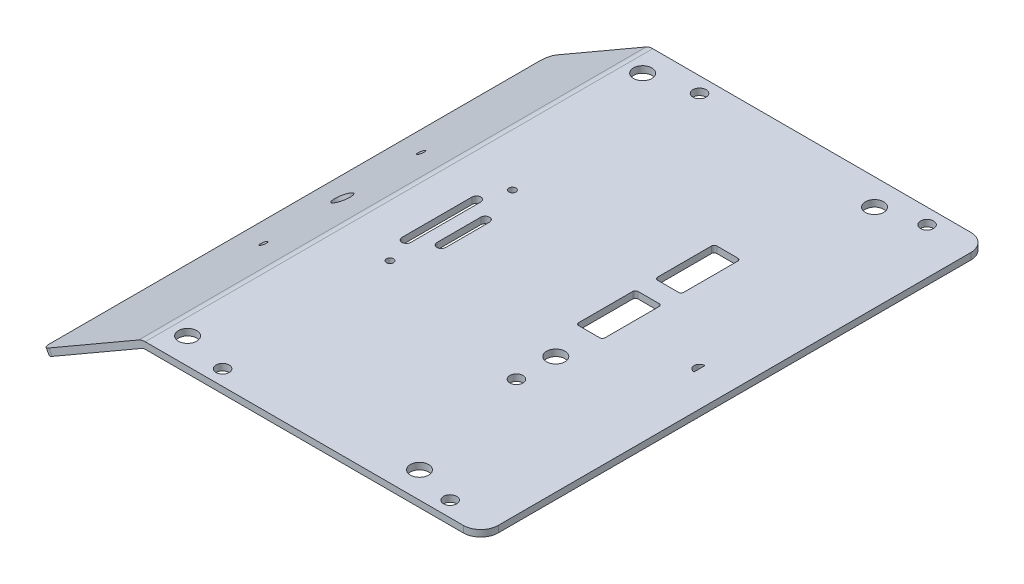
SolidWorks part; units mm, degrees
ref_plane "Alzado" through (0, 0, 0) normal (0, 0, 1) x (1, 0, 0)
ref_plane "Planta" through (0, 0, 0) normal (0, 1, 0) x (1, 0, 0)
ref_plane "Vista lateral" through (0, 0, 0) normal (1, 0, 0) x (0, 0, -1)
ref_plane "Plano1" through (0, 0, -57) normal (0, 0, -1) x (-1, 0, 0)
sketch "Croquis1" plane through (0, 0, -57) normal (0, 0, -1) x (-1, 0, 0)
  line L0 (58.4497, -13.25) -> (35.5, 0)
  line L1 (35.5, 0) -> (-38, 0)
  line L2 (-38, 0) -> (-38, -1.5)
  line L3 (-38, -1.5) -> (35.0981, -1.5)
  line L4 (35.0981, -1.5) -> (57.6997, -14.549)
  line L5 (57.6997, -14.549) -> (58.4497, -13.25)
extrude "Saliente-Extruir1" add sketch "Croquis1" against normal blind 116
sketch "Croquis2" plane through (0, 0, 0) normal (0, 1, 0) x (-1, 0, 0)
  line L0 (-17.07, -25.275) -> (-11.07, -25.275)
  line L1 (-11.07, -25.275) -> (-11.07, -11.725)
  line L2 (-11.07, -11.725) -> (-17.07, -11.725)
  line L3 (-17.07, -11.725) -> (-17.07, -25.275)
extrude "Cortar-Extruir1" cut sketch "Croquis2" against normal through all
sketch "Croquis3" plane through (0, 0, 0) normal (0, 1, 0) x (-1, 0, 0)
  line L0 (-11.07, -7.275) -> (-11.07, 6.275)
  line L1 (-11.07, 6.275) -> (-17.07, 6.275)
  line L2 (-17.07, 6.275) -> (-17.07, -7.275)
  line L3 (-17.07, -7.275) -> (-11.07, -7.275)
extrude "Cortar-Extruir2" cut sketch "Croquis3" against normal through all
sketch "Croquis4" plane through (0, 0, 0) normal (0, 1, 0) x (-1, 0, 0)
  line L0 (21, -4) -> (21, 6)
  line L1 (19, 6) -> (19, -4)
  arc A0 (19, -4) -> (21, -4) centre (20, -4) ccw
  arc A1 (21, 6) -> (19, 6) centre (20, 6) ccw
extrude "Cortar-Extruir3" cut sketch "Croquis4" against normal through all
sketch "Croquis5" plane through (0, -1.5, 0) normal (0, -1, 0) x (1, 0, 0)
  line L0 (-24, -7) -> (-24, 9)
  line L1 (-26, 9) -> (-26, -7)
  arc A0 (-26, -7) -> (-24, -7) centre (-25, -7) ccw
  arc A1 (-24, 9) -> (-26, 9) centre (-25, 9) ccw
extrude "Cortar-Extruir4" cut sketch "Croquis5" against normal through all
hole_wizard "Diámetro de taladro Ø2.5 (2.5)1" positions "Croquis7" profile "Croquis6" hole size "Ø2.5" standard "Ansi Metric"
sketch "Croquis7" plane through (0, -1.5, 0) normal (0, -1, 0) x (-1, 0, 0)
  point P0 (-34, -1)
sketch "Croquis6" plane through (34, -1.5, 1) normal (1, 0, 0) x (0, 0, -1)
  line L0 (0, 0) -> (0, 1.5)
  line L1 (0, 1.5) -> (1.25, 1.5)
  line L2 (1.25, 1.5) -> (1.25, 0)
  line L5 (1.25, 0) -> (0, 0)
  line L11 (0, -6.35) -> (0, 107.95) construction
  dimension "Diámetro de taladro hasta el siguiente" = 2.5
  dimension "Profundidad de taladro hasta el siguiente" = 1.5
hole_wizard "Diámetro de taladro Ø3.0 (3)1" positions "Croquis9" profile "Croquis8" hole size "Ø3.0" standard "Ansi Metric"
sketch "Croquis9" plane through (0, -1.5, 0) normal (0, -1, 0) x (-1, 0, 0)
  point P0 (-15.15, -24)
  point P1 (-31.5, 53.5)
  point P2 (20.5, -55.5)
  point P3 (-31.5, -55.5)
  point P4 (20.5, 53.5)
sketch "Croquis8" plane through (15.15, -1.5, 24) normal (1, 0, 0) x (0, 0, -1)
  line L0 (0, 0) -> (0, 1.5)
  line L1 (0, 1.5) -> (1.5, 1.5)
  line L2 (1.5, 1.5) -> (1.5, 0)
  line L5 (1.5, 0) -> (0, 0)
  line L11 (0, -6.35) -> (0, 107.95) construction
  dimension "Diámetro de taladro hasta el siguiente" = 3
  dimension "Profundidad de taladro hasta el siguiente" = 1.5
hole_wizard "Diámetro de taladro Ø1.6 (1.6)1" positions "Croquis11" profile "Croquis10" hole size "Ø1.6" standard "Ansi Metric"
sketch "Croquis11" plane through (0, -1.5, 0) normal (0, -1, 0) x (-1, 0, 0)
  point P0 (22.75, -15)
  point P1 (22.75, 13)
sketch "Croquis10" plane through (-22.75, -1.5, 15) normal (1, 0, 0) x (0, 0, -1)
  line L0 (0, 0) -> (0, 1.5)
  line L1 (0, 1.5) -> (0.8, 1.5)
  line L2 (0.8, 1.5) -> (0.8, 0)
  line L5 (0.8, 0) -> (0, 0)
  line L11 (0, -6.35) -> (0, 107.95) construction
  dimension "Diámetro de taladro hasta el siguiente" = 1.6
  dimension "Profundidad de taladro hasta el siguiente" = 1.5
hole_wizard "Diámetro de taladro Ø4.0 (4)1" positions "Croquis13" profile "Croquis12" hole size "Ø4.0" standard "Ansi Metric"
sketch "Croquis13" plane through (-8.125, 14.0729, 0) normal (0.5, -0.866, 0) x (-0.866, -0.5, 0)
  point P0 (44.7439, -1)
sketch "Croquis12" plane through (-46.8744, -8.299, 1) normal (0, 0, 1) x (0.866, 0.5, 0)
  line L0 (0, 0) -> (0, 12.9748)
  line L1 (0, 12.9748) -> (2, 12.9748)
  line L2 (2, 12.9748) -> (2, 0)
  line L5 (2, 0) -> (0, 0)
  line L11 (0, -6.35) -> (0, 107.95) construction
  dimension "Diámetro de taladro hasta el siguiente" = 4
  dimension "Profundidad de taladro hasta el siguiente" = 12.9748
hole_wizard "Diámetro de taladro Ø1.6 (1.6)2" positions "Croquis15" profile "Croquis14" hole size "Ø1.6" standard "Ansi Metric"
sketch "Croquis15" plane through (-8.125, 14.0729, 0) normal (0.5, -0.866, 0) x (-0.866, -0.5, 0)
  point P0 (44.7439, -19)
  point P1 (44.7439, 17)
sketch "Croquis14" plane through (-46.8744, -8.299, 19) normal (0, 0, 1) x (0.866, 0.5, 0)
  line L0 (0, 0) -> (0, 12.9748)
  line L1 (0, 12.9748) -> (0.8, 12.9748)
  line L2 (0.8, 12.9748) -> (0.8, 0)
  line L5 (0.8, 0) -> (0, 0)
  line L11 (0, -6.35) -> (0, 107.95) construction
  dimension "Diámetro de taladro hasta el siguiente" = 1.6
  dimension "Profundidad de taladro hasta el siguiente" = 12.9748
hole_wizard "Diámetro de taladro Ø4.2 (4.2)1" positions "Croquis17" profile "Croquis16" hole size "Ø4.2" standard "Ansi Metric"
sketch "Croquis17" plane through (0, -1.5, 0) normal (0, -1, 0) x (-1, 0, 0)
  point P0 (31, -53)
  point P1 (31, 51)
  point P2 (-22, -53)
  point P3 (-22, 51)
  point P4 (-15.15, -15)
sketch "Croquis16" plane through (-31, -1.5, 53) normal (1, 0, 0) x (0, 0, -1)
  line L0 (0, 0) -> (0, 1.5)
  line L1 (0, 1.5) -> (2.1, 1.5)
  line L2 (2.1, 1.5) -> (2.1, 0)
  line L5 (2.1, 0) -> (0, 0)
  line L11 (0, -6.35) -> (0, 107.95) construction
  dimension "Diámetro de taladro hasta el siguiente" = 4.2
  dimension "Profundidad de taladro hasta el siguiente" = 1.5
fillet "Redondeo1" radius 0.6 8 edges at (17.07, -0.75, -25.275) (17.07, -0.75, 6.275) (17.07, -0.75, -7.275) (11.07, -0.75, -11.725) (11.07, -0.75, -7.275) (11.07, -0.75, 6.275) (11.07, -0.75, -25.275) (17.07, -0.75, -11.725)
fillet "Redondeo2" radius 1.5 1 edges at (-35.0981, -1.5, 1)
fillet "Redondeo3" radius 2 4 edges at (-58.0747, -13.8995, 59) (38, -0.75, 59) (-58.0747, -13.8995, -57) (38, -0.75, -57)
fillet "Redondeo4" radius 3 1 edges at (-35.5, 0, 1)
sketch "Croquis18" plane through (38, 0, 0) normal (1, 0, 0) x (0, 0, -1)
  line L1 (-59, 0) -> (57, 0)
  line L2 (-59, 0) -> (-59, -1.5)
  line L3 (-59, -1.5) -> (57, -1.5)
  line L4 (57, 0) -> (57, -1.5)
extrude "Saliente-Extruir2" add sketch "Croquis18" along normal blind 4 and the other way blind 4
fillet "Redondeo5" radius 4 2 edges at (42, -0.75, 59) (42, -0.75, -57)
